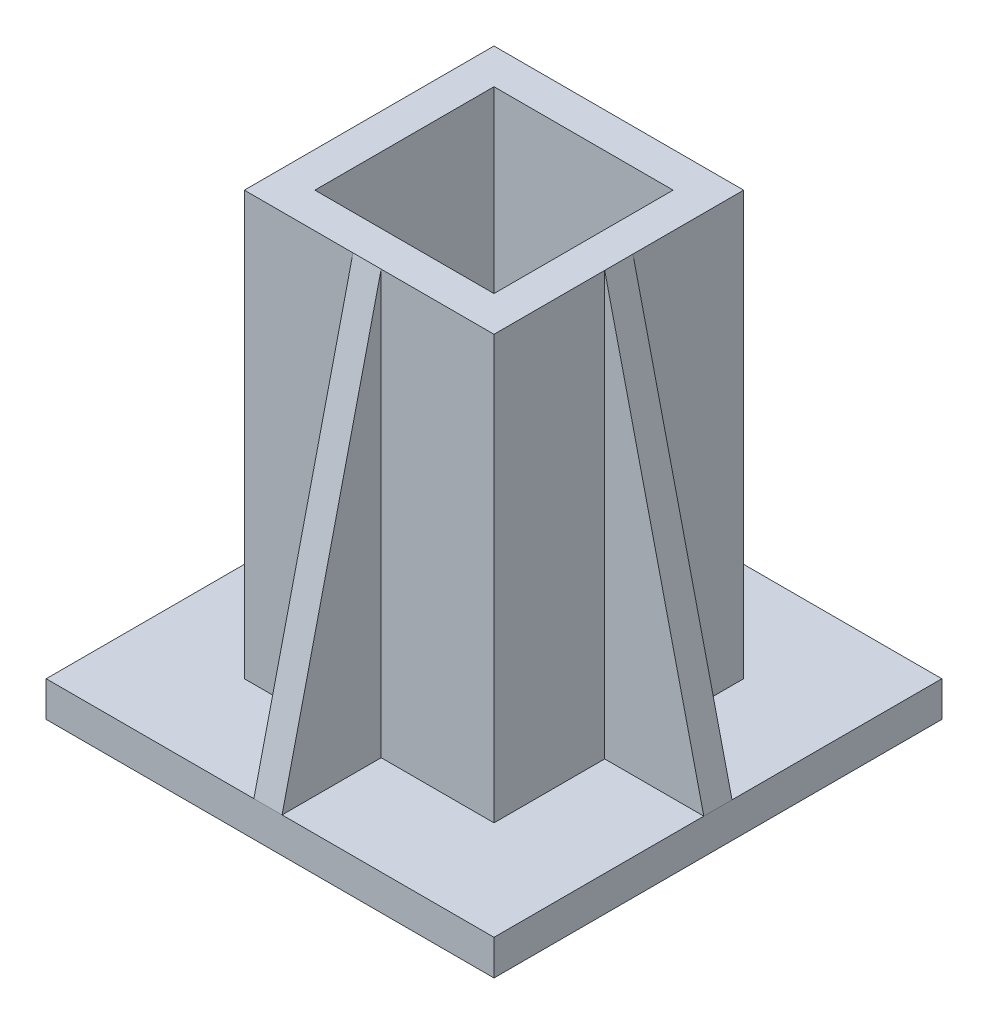
SolidWorks part; units mm, degrees
ref_plane "Front Plane" through (0, 0, 0) normal (0, 0, 1) x (1, 0, 0)
ref_plane "Top Plane" through (0, 0, 0) normal (0, 1, 0) x (1, 0, 0)
ref_plane "Right Plane" through (0, 0, 0) normal (1, 0, 0) x (0, 0, -1)
sketch "Sketch1" plane through (0, 0, 0) normal (0, 1, 0) x (1, 0, 0)
  line L1 (31.75, 31.75) -> (-31.75, 31.75)
  line L2 (31.75, 31.75) -> (31.75, -31.75)
  line L3 (31.75, -31.75) -> (-31.75, -31.75)
  line L4 (-31.75, 31.75) -> (-31.75, -31.75)
  line L5 (31.75, 31.75) -> (-31.75, -31.75) construction
  line L6 (31.75, -31.75) -> (-31.75, 31.75) construction
  point P0 (0, 0)
  dimension "D1" = 63.5
  dimension "D2" = 63.5
extrude "Boss-Extrude1" add sketch "Sketch1" along normal blind 5
sketch "Sketch2" plane through (0, 5, 0) normal (0, 1, 0) x (1, 0, 0)
  line L0 (17.7, 17.7) -> (-17.7, 17.7)
  line L1 (12.7, -12.7) -> (-12.7, -12.7)
  line L2 (12.7, -12.7) -> (12.7, 12.7)
  line L3 (12.7, 12.7) -> (-12.7, 12.7)
  line L4 (-12.7, -12.7) -> (-12.7, 12.7)
  line L5 (12.7, -12.7) -> (-12.7, 12.7) construction
  line L6 (12.7, 12.7) -> (-12.7, -12.7) construction
  line L7 (-17.7, -17.7) -> (-17.7, 17.7)
  line L8 (17.7, -17.7) -> (-17.7, -17.7)
  line L9 (17.7, -17.7) -> (17.7, 17.7)
  point P0 (0, 0)
  dimension "D3" = 5
  dimension "D1" = 25.4
  dimension "D2" = 25.4
extrude "Boss-Extrude2" add sketch "Sketch2" along normal blind 60
ref_plane "Plane2" through (0, 0, 0) normal (0, 0, 1) x (1, 0, 0)
sketch "Sketch11" plane through (0, 0, 0) normal (0, 0, 1) x (1, 0, 0)
  line L0 (-17.7, 65) -> (-31.75, 5)
sketch "Sketch13" plane through (0, 5, 0) normal (0, 1, 0) x (1, 0, 0)
  line L0 (-31.75, 31.75) -> (-31.75, -31.75) construction
  line L1 (-31.75, 2) -> (-17.7, 2)
  line L2 (-31.75, 2) -> (-31.75, -2)
  line L3 (-31.75, -2) -> (-17.7, -2)
  line L4 (-17.7, 2) -> (-17.7, -2)
  line L5 (-17.7, 17.7) -> (-17.7, -17.7) construction
  line L6 (-17.7, 0) -> (-31.75, 0) construction
  point P8 (0, 0)
  dimension "D1" = 2
  dimension "D2" = 2
extrude "Boss-Extrude3" add sketch "Sketch13" along normal blind 60
sketch "Sketch14" plane through (0, 0, 2) normal (0, 0, 1) x (1, 0, 0)
  line L0 (-31.75, 5) -> (-17.7, 65)
extrude "Cut-Extrude1" cut sketch "Sketch14" against normal through all and the other way through all contours L0
sketch "Sketch15" plane through (0, 5, 0) normal (0, 1, 0) x (1, 0, 0)
  line L0 (17.7, -17.7) -> (17.7, 17.7) construction
  line L1 (17.7, 2) -> (31.75, 2)
  line L2 (17.7, 2) -> (17.7, -2)
  line L3 (17.7, -2) -> (31.75, -2)
  line L4 (31.75, 2) -> (31.75, -2)
  line L5 (31.75, -31.75) -> (31.75, 31.75) construction
  line L6 (-19.47, 0) -> (19.47, 0) construction
  dimension "D1" = 2
  dimension "D2" = 2
extrude "Boss-Extrude4" add sketch "Sketch15" along normal blind 60
sketch "Sketch16" plane through (0, 0, 2) normal (0, 0, 1) x (1, 0, 0)
  line L0 (31.75, 5) -> (17.7, 65)
extrude "Cut-Extrude3" cut sketch "Sketch16" against normal through all and the other way through all flip side to cut
sketch "Sketch17" plane through (0, 5, 0) normal (0, 1, 0) x (1, 0, 0)
  line L0 (-17.7, -17.7) -> (17.7, -17.7) construction
  line L1 (-2.3, -17.7) -> (1.7, -17.7)
  line L2 (-2.3, -17.7) -> (-2.3, -31.75)
  line L3 (-2.3, -31.75) -> (1.7, -31.75)
  line L4 (1.7, -17.7) -> (1.7, -31.75)
  line L5 (-31.75, -31.75) -> (31.75, -31.75) construction
  dimension "D1" = 15.4
  dimension "D2" = 4
extrude "Boss-Extrude5" add sketch "Sketch17" along normal blind 60
sketch "Sketch18" plane through (-2.3, 0, 0) normal (-1, 0, 0) x (0, 0, 1)
  line L0 (31.75, 5) -> (17.7, 65)
extrude "Cut-Extrude4" cut sketch "Sketch18" against normal through all and the other way through all flip side to cut
sketch "Sketch21" plane through (0, 0, -17.7) normal (0, 0, -1) x (-1, 0, 0)
  circle A0 centre (0, 17.7394) radius 3.175
  circle A1 centre (0, 47.4664) radius 3.175
  dimension "D1" = 6.35
extrude "Cut-Extrude7" cut sketch "Sketch21" against normal blind 20
